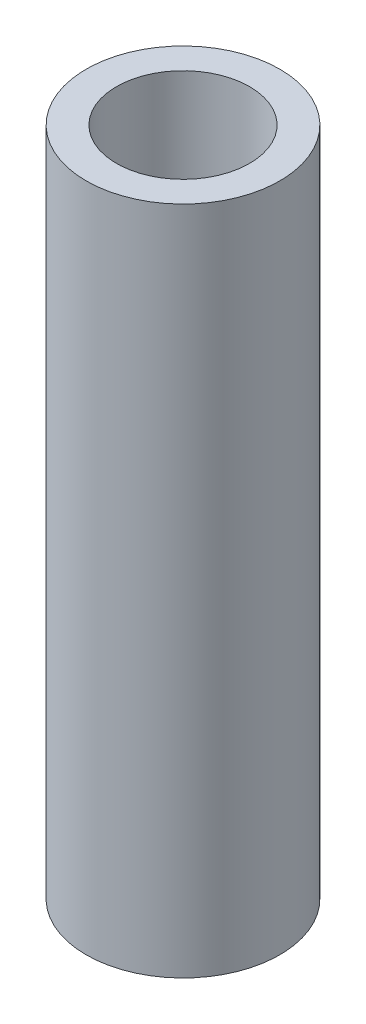
SolidWorks part; units mm, degrees
material "Corrugated Paper"
ref_plane "Front Plane" through (0, 0, 0) normal (0, 0, 1) x (1, 0, 0)
ref_plane "Top Plane" through (0, 0, 0) normal (0, 1, 0) x (1, 0, 0)
ref_plane "Right Plane" through (0, 0, 0) normal (1, 0, 0) x (0, 0, -1)
sketch "Sketch1" plane through (0, 0, 0) normal (0, 1, 0) x (1, 0, 0)
  circle A0 centre (0, 0) radius 6.5
  circle A1 centre (0, 0) radius 4.468
  dimension "D1" = 13
  dimension "D2" = 2.032
extrude "Boss-Extrude1" add sketch "Sketch1" along normal blind 45
